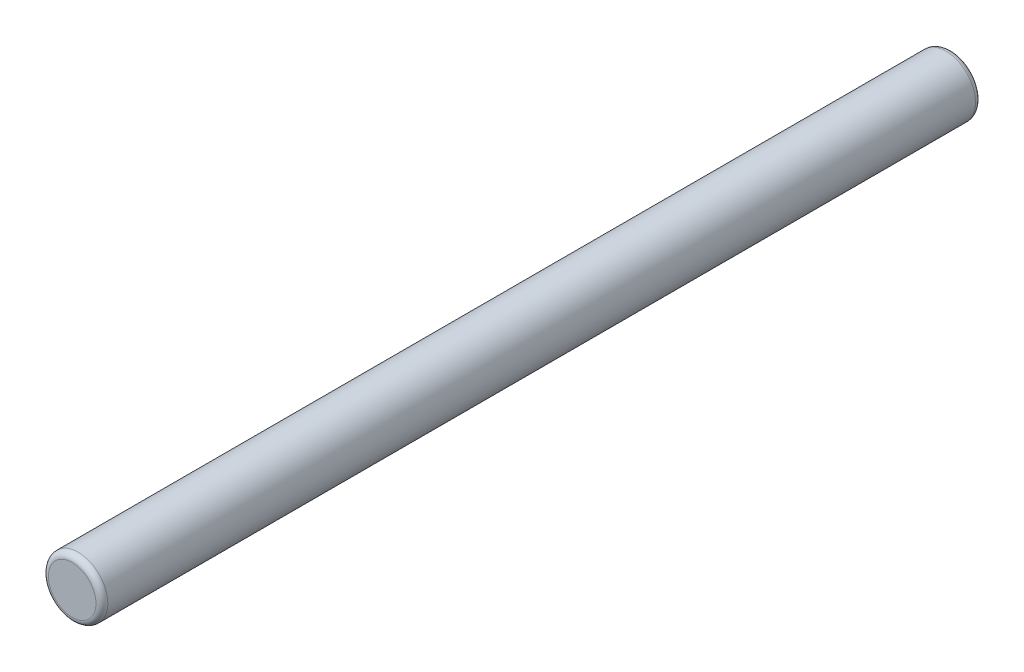
SolidWorks part; units mm, degrees
ref_plane "Front Plane" through (0, 0, 0) normal (0, 0, 1) x (1, 0, 0)
ref_plane "Top Plane" through (0, 0, 0) normal (0, 1, 0) x (1, 0, 0)
ref_plane "Right Plane" through (0, 0, 0) normal (1, 0, 0) x (0, 0, -1)
sketch "Sketch1" plane through (0, 0, 0) normal (0, 0, 1) x (1, 0, 0)
  circle A0 centre (0, 0) radius 0.5
  dimension "D1" = 1
extrude "Boss-Extrude1" add sketch "Sketch1" along normal mid plane 14.8
fillet "Fillet1" radius 0.1 2 edges at (0.5, 0, 7.4) (0.5, 0, -7.4)
